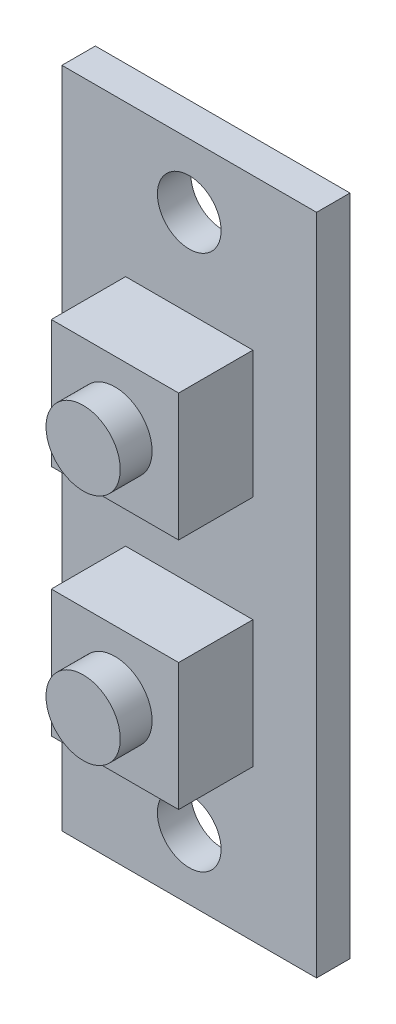
SolidWorks part; units mm, degrees
ref_plane "Front Plane" through (0, 0, 0) normal (0, 0, 1) x (1, 0, 0)
ref_plane "Top Plane" through (0, 0, 0) normal (0, 1, 0) x (1, 0, 0)
ref_plane "Right Plane" through (0, 0, 0) normal (1, 0, 0) x (0, 0, -1)
sketch "Sketch1" plane through (0, 0, 0) normal (0, 0, 1) x (1, 0, 0)
  line L1 (-6.096, -15.875) -> (6.096, -15.875)
  line L2 (-6.096, -15.875) -> (-6.096, 15.875)
  line L3 (-6.096, 15.875) -> (6.096, 15.875)
  line L4 (6.096, -15.875) -> (6.096, 15.875)
  line L5 (-6.096, -15.875) -> (6.096, 15.875) construction
  line L6 (-6.096, 15.875) -> (6.096, -15.875) construction
  point P0 (0, 0)
  dimension "D1" = 12.192
  dimension "D2" = 31.75
extrude "Boss-Extrude1" add sketch "Sketch1" along normal blind 1.6002
sketch "Sketch2" plane through (0, 0, 1.6002) normal (0, 0, 1) x (1, 0, 0)
  line L0 (0, 0) -> (0, -2.54) construction
  line L1 (0, 0) -> (0, 2.54) construction
  line L3 (-3.048, 2.54) -> (3.048, 2.54)
  line L4 (-3.048, 2.54) -> (-3.048, 8.636)
  line L5 (-3.048, 8.636) -> (3.048, 8.636)
  line L6 (3.048, 2.54) -> (3.048, 8.636)
  line L7 (-3.048, -2.54) -> (3.048, -2.54)
  line L8 (-3.048, -2.54) -> (-3.048, -8.636)
  line L9 (-3.048, -8.636) -> (3.048, -8.636)
  line L10 (3.048, -2.54) -> (3.048, -8.636)
  point P13 (0, 2.54)
  point P14 (0, -2.54)
  dimension "D1" = 2.54
  dimension "D2" = 6.096
extrude "Boss-Extrude2" add sketch "Sketch2" along normal blind 3.556
sketch "Sketch3" plane through (0, 0, 5.1562) normal (0, 0, 1) x (1, 0, 0)
  line L0 (-3.048, 8.636) -> (3.048, 2.54) construction
  line L1 (-3.048, -2.54) -> (3.048, -8.636) construction
  circle A0 centre (0, 5.588) radius 1.778
  circle A1 centre (0, -5.588) radius 1.778
  dimension "D1" = 3.556
extrude "Boss-Extrude3" add sketch "Sketch3" along normal blind 1.524
sketch "Sketch4" plane through (0, 0, 1.6002) normal (0, 0, 1) x (1, 0, 0)
  line L0 (0, 12.827) -> (0, 15.875) construction
  line L3 (0, -12.827) -> (0, -15.875) construction
  line L6 (6.096, 15.875) -> (-6.096, 15.875) construction
  line L7 (-6.096, -15.875) -> (6.096, -15.875) construction
  circle A0 centre (0, 12.827) radius 1.524
  circle A1 centre (0, -12.827) radius 1.524
  point P6 (0, 0)
  dimension "D1" = 3.048
  dimension "D2" = 3.048
  dimension "D3" = 3.048
extrude "Cut-Extrude1" cut sketch "Sketch4" against normal through all both and the other way through all
